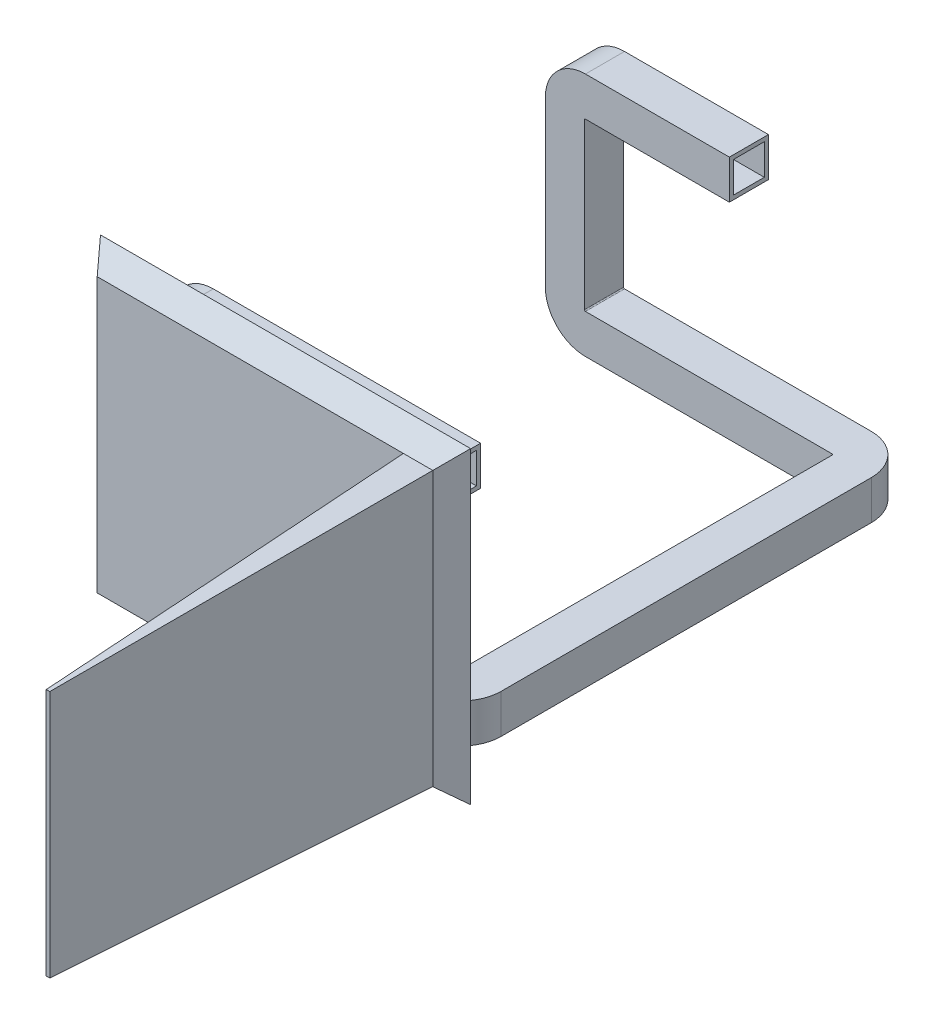
SolidWorks part; units mm, degrees
ref_plane "Front Plane" through (0, 0, 0) normal (0, 0, 1) x (1, 0, 0)
ref_plane "Top Plane" through (0, 0, 0) normal (0, 1, 0) x (1, 0, 0)
ref_plane "Right Plane" through (0, 0, 0) normal (1, 0, 0) x (0, 0, -1)
sketch3d "3DSketch1"
  line L0 (0, 0, 0) -> (-70, 0, 0)
  line L1 (-80, -10, 0) -> (-80, -90, 0)
  line L2 (-70, -100, 0) -> (50, -100, 0)
  line L3 (60, -100, 10) -> (60, -100, 190)
  line L4 (50, -100, 200) -> (-70, -100, 200)
  line L5 (-80, -90, 200) -> (-80, -10, 200)
  line L6 (-70, 0, 200) -> (60, 0, 200)
  arc A0 (-80, -10, 200) -> (-70, 0, 200) centre (-70, -10, 200) ccw
  arc A1 (-70, -100, 200) -> (-80, -90, 200) centre (-70, -90, 200) ccw
  arc A2 (60, -100, 190) -> (50, -100, 200) centre (50, -100, 190) ccw
  arc A3 (50, -100, 0) -> (60, -100, 10) centre (50, -100, 10) ccw
  arc A4 (-80, -90, 0) -> (-70, -100, 0) centre (-70, -90, 0) ccw
  arc A5 (-70, 0, 0) -> (-80, -10, 0) centre (-70, -10, 0) ccw
  point P11 (-80, 0, 200)
  point P12 (-70, -10, 190)
  point P15 (-80, -100, 200)
  point P16 (-70, -90, 190)
  point P19 (60, -100, 200)
  point P20 (50, -110, 190)
  point P23 (60, -100, 0)
  point P24 (50, -110, 10)
  point P27 (-80, -100, 0)
  point P28 (-70, -90, 10)
  point P31 (-80, 0, 0)
  point P32 (-70, -10, 10)
  dimension "D8" = 10
  dimension "D1" = 80
  dimension "D2" = 100
  dimension "D3" = 140
  dimension "D4" = 200
  dimension "D5" = 140
  dimension "D6" = 100
  dimension "D7" = 140
sketch "Sketch2" plane through (0, 0, 0) normal (1, 0, 0) x (0, 0, -1)
  line L1 (-7.5, -7.5) -> (7.5, -7.5)
  line L2 (-7.5, -7.5) -> (-7.5, 7.5)
  line L3 (-7.5, 7.5) -> (7.5, 7.5)
  line L4 (7.5, -7.5) -> (7.5, 7.5)
  line L5 (-7.5, -7.5) -> (7.5, 7.5) construction
  line L6 (-7.5, 7.5) -> (7.5, -7.5) construction
  point P0 (0, 0)
  dimension "D1" = 15
  dimension "D2" = 15
sweep "Sweep-Thin1" add profiles "Sketch2" path "3DSketch1" parameters "D1"=2
sketch "Sketch3" plane through (0, 0, 209.5) normal (0, 0, 1) x (1, 0, 0)
  line L0 (-105.849, 23.8119) -> (74.151, 23.8119)
  line L1 (-105.849, 23.8119) -> (-105.849, -126.1881)
  line L2 (74.151, 23.8119) -> (74.151, -126.1881)
  line L3 (-105.849, -126.1881) -> (74.151, -126.1881)
  dimension "D1" = 150
  dimension "D2" = 180
extrude "Boss-Extrude1" add sketch "Sketch3" along normal blind 10 draft 40
sketch "Sketch4" plane through (0, 0, 219.5) normal (0, 0, 1) x (1, 0, 0)
  line L0 (65.76, 15.4209) -> (65.76, -117.7971)
  line L1 (65.76, 15.4209) -> (51.4772, 15.4209)
  line L2 (65.76, -117.7971) -> (51.4772, -117.7971)
  line L3 (51.4772, 15.4209) -> (51.4772, -117.7971)
extrude "Boss-Extrude2" add sketch "Sketch4" along normal blind 180 draft 2
